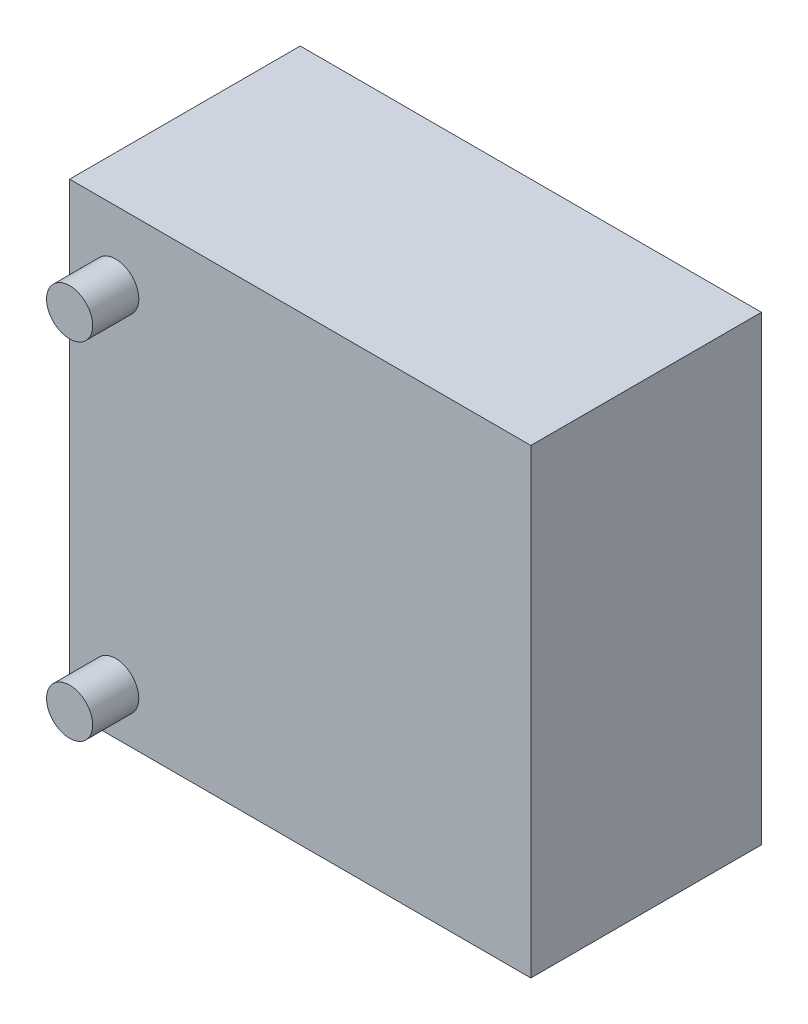
SolidWorks part; units mm, degrees
ref_plane "前视基准面" through (0, 0, 0) normal (0, 0, 1) x (1, 0, 0)
ref_plane "上视基准面" through (0, 0, 0) normal (0, 1, 0) x (1, 0, 0)
ref_plane "右视基准面" through (0, 0, 0) normal (1, 0, 0) x (0, 0, -1)
other "Configuration Table"
sketch "草图1" plane through (0, 0, 0) normal (0, 0, 1) x (1, 0, 0)
  line L1 (0, 0) -> (20, 0)
  line L2 (0, 0) -> (0, 20)
  line L3 (0, 20) -> (20, 20)
  line L4 (20, 0) -> (20, 20)
extrude "BaseBox" add sketch "草图1" along normal blind 10
sketch "草图2" plane through (0, 0, 10) normal (0, 0, 1) x (1, 0, 0)
  circle A0 centre (2, 2) radius 1
extrude "BossSeed" add sketch "草图2" along normal blind 2
pattern_linear "LinearPattern" count 2 spacing 10 along (-1, 0, 0) count 3 spacing 15 along (0, 1, 0) of "BossSeed"
